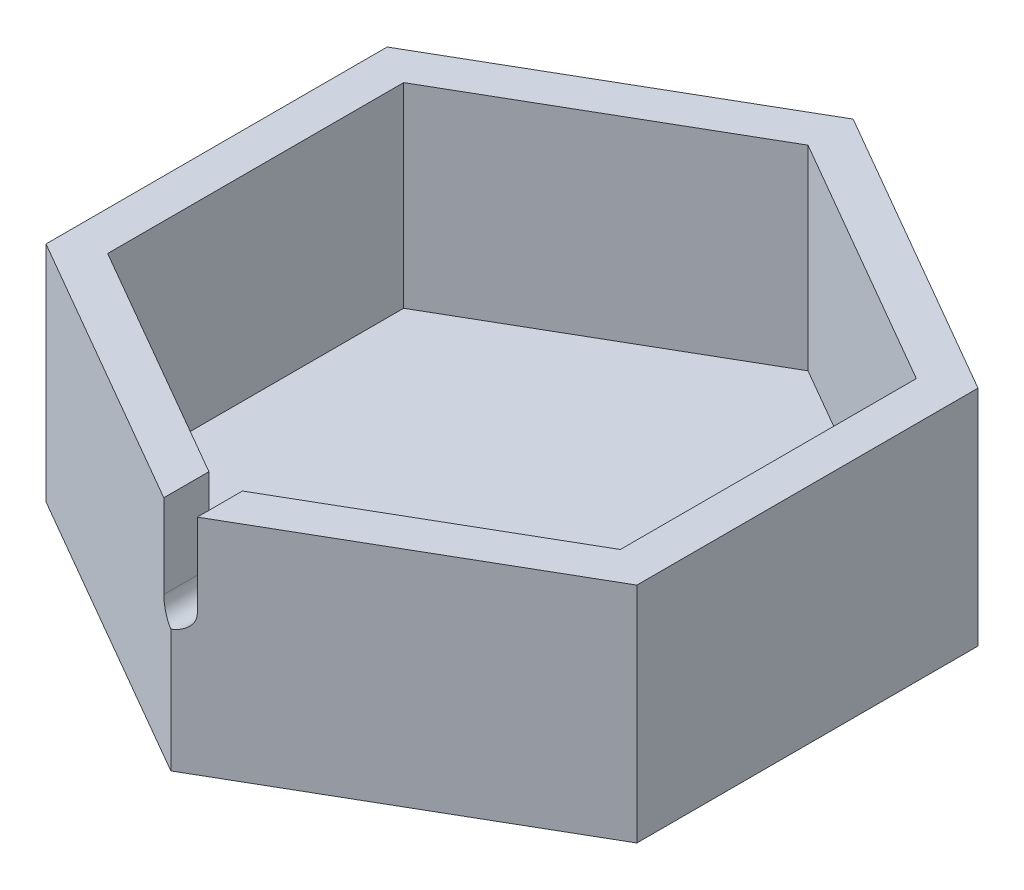
SolidWorks part; units mm, degrees
ref_plane "Front Plane" through (0, 0, 0) normal (0, 0, 1) x (1, 0, 0)
ref_plane "Top Plane" through (0, 0, 0) normal (0, 1, 0) x (1, 0, 0)
ref_plane "Right Plane" through (0, 0, 0) normal (1, 0, 0) x (0, 0, -1)
sketch "Sketch2" plane through (0, 0, 0) normal (0, 1, 0) x (1, 0, 0)
  line L1 (52.9051, -30.5448) -> (52.9051, 30.5448)
  line L2 (52.9051, 30.5448) -> (0, 61.0895)
  line L3 (0, 61.0895) -> (-52.9051, 30.5448)
  line L4 (-52.9051, 30.5448) -> (-52.9051, -30.5448)
  line L5 (-52.9051, -30.5448) -> (0, -61.0896)
  line L6 (0, -61.0896) -> (52.9051, -30.5448)
  line L7 (45.9051, -26.5033) -> (45.9051, 26.5033)
  line L8 (45.9051, 26.5033) -> (0, 53.0066)
  line L9 (0, 53.0066) -> (-45.9051, 26.5033)
  line L10 (-45.9051, 26.5033) -> (-45.9051, -26.5033)
  line L11 (-45.9051, -26.5033) -> (0, -53.0066)
  line L12 (0, -53.0066) -> (45.9051, -26.5033)
  circle A0 centre (0, 0) radius 45.9051 construction
  dimension "D1" = 122.1791
  dimension "D2" = 7
extrude "Boss-Extrude1" add sketch "Sketch2" along normal blind 40
sketch "Sketch7" plane through (0, 0, 0) normal (0, -1, 0) x (1, 0, 0)
  line L0 (52.9051, 30.5448) -> (52.9051, -30.5448) construction
  line L1 (-49.4051, 28.524) -> (-49.4051, -28.524)
  line L2 (-49.4051, -28.524) -> (0, -57.0481)
  line L3 (0, -57.0481) -> (49.4051, -28.524)
  line L4 (49.4051, -28.524) -> (49.4051, 28.524)
  line L5 (49.4051, 28.524) -> (0, 57.0481)
  line L6 (0, 57.0481) -> (-49.4051, 28.524)
  circle A0 centre (0, 0) radius 49.4051 construction
  dimension "D1" = 3.5
extrude "Boss-Extrude5" add sketch "Sketch7" against normal blind 5
ref_plane "Plane4" through (0, 0, 61) normal (0, 0, 1) x (1, 0, 0)
sketch "Sketch8" plane through (0, 0, 61) normal (0, 0, 1) x (1, 0, 0)
  line L0 (0, 40) -> (52.9051, 40) construction
  line L1 (3, 40) -> (3, 25)
  line L2 (-52.9051, 40) -> (0, 40) construction
  line L3 (-3, 40) -> (-3, 25)
  line L4 (-3, 40) -> (0, 40)
  line L5 (0, 40) -> (3, 40)
  line L6 (0, 40) -> (0, 0) construction
  arc A0 (3, 25) -> (0, 22) centre (0, 25) cw
  arc A1 (0, 22) -> (-3, 25) centre (0, 25) cw
  dimension "D1" = 3
  dimension "D2" = 15
  dimension "3" = 3
  dimension "D3" = 15
extrude "Cut-Extrude2" cut sketch "Sketch8" against normal mid plane 39
